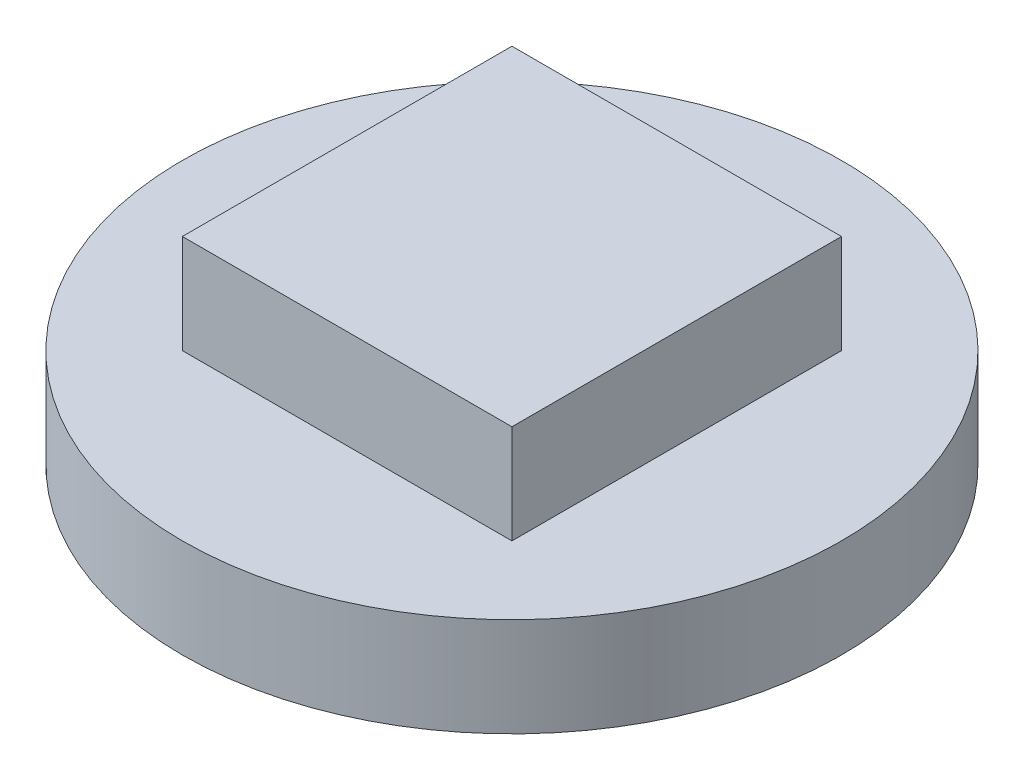
SolidWorks part; units mm, degrees
ref_plane "Спереди" through (0, 0, 0) normal (0, 0, 1) x (1, 0, 0)
ref_plane "Сверху" through (0, 0, 0) normal (0, 1, 0) x (1, 0, 0)
ref_plane "Справа" through (0, 0, 0) normal (1, 0, 0) x (0, 0, -1)
sketch "Эскиз1" plane through (0, 0, 0) normal (0, 1, 0) x (1, 0, 0)
  circle A0 centre (0, 0) radius 5
  dimension "D1" = 10
extrude "Бобышка-Вытянуть1" add sketch "Эскиз1" along normal blind 1.5
sketch "Эскиз2" plane through (0, 0, 0) normal (0, 1, 0) x (1, 0, 0)
  line L0 (0, 2.5) -> (0, -2.5) construction
  line L1 (-2.5, 2.5) -> (2.5, 2.5)
  line L2 (-2.5, 2.5) -> (-2.5, -2.5)
  line L3 (-2.5, -2.5) -> (2.5, -2.5)
  line L4 (2.5, 2.5) -> (2.5, -2.5)
  point P6 (0, 0)
  dimension "D1" = 5
extrude "Бобышка-Вытянуть2" add sketch "Эскиз2" along normal blind 3
